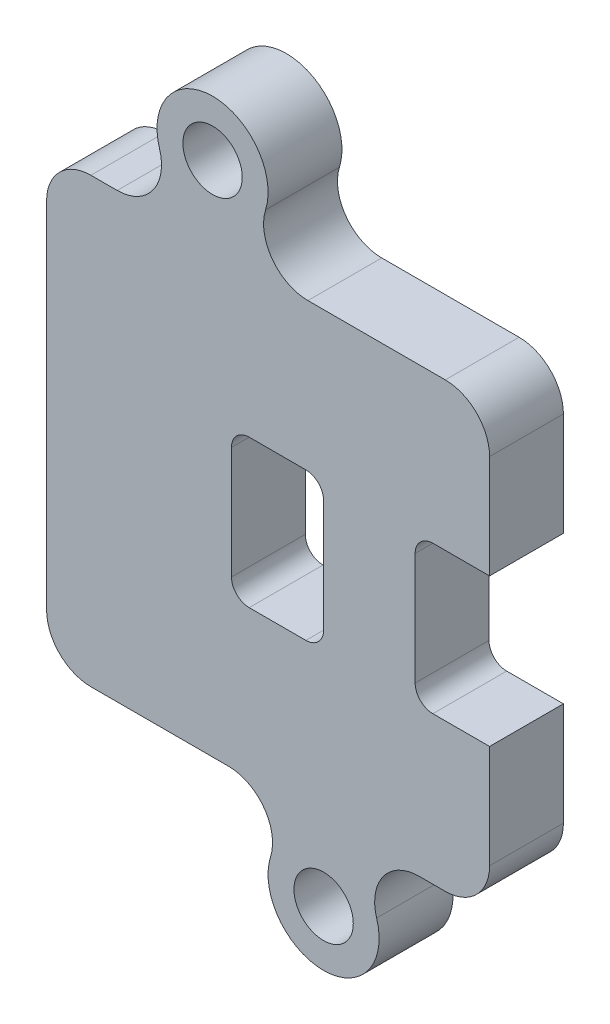
SolidWorks part; units mm, degrees
ref_plane "Front Plane" through (0, 0, 0) normal (0, 0, 1) x (1, 0, 0)
ref_plane "Top Plane" through (0, 0, 0) normal (0, 1, 0) x (1, 0, 0)
ref_plane "Right Plane" through (0, 0, 0) normal (1, 0, 0) x (0, 0, -1)
sketch "Sketch1" plane through (0, 0, 0) normal (0, 0, 1) x (1, 0, 0)
  line L0 (0, 0) -> (38.9585, 0) construction
  line L1 (0, 0) -> (0, -11.6692) construction
  line L2 (0, 0) -> (0, 50.8) construction
  line L3 (-9.5504, 50.8) -> (38.9585, 50.8) construction
  line L4 (-20.0152, 44.45) -> (-17.7513, 44.45)
  line L5 (-23.8252, 40.64) -> (-23.8252, 10.16)
  line L6 (-20.0152, 6.35) -> (-8.2009, 6.35)
  line L7 (14.2748, 40.64) -> (14.2748, 10.16)
  line L8 (-9.5504, 50.8) -> (-9.5504, 15.7719) construction
  line L9 (14.2748, 6.35) -> (14.2748, -14.1884) construction
  line L10 (-7.9248, 31.75) -> (-7.9248, 36.7665) construction
  line L11 (-6.4008, 31.75) -> (-1.524, 31.75)
  line L12 (-7.9248, 30.226) -> (-7.9248, 20.574)
  line L13 (-6.4008, 19.05) -> (-1.524, 19.05)
  line L14 (0, 30.226) -> (0, 20.574)
  line L15 (9.398, 31.75) -> (14.2748, 31.75)
  line L16 (7.874, 30.226) -> (7.874, 20.574)
  line L17 (9.398, 19.05) -> (14.2748, 19.05)
  line L18 (14.2748, 31.75) -> (14.2748, 19.05)
  line L19 (14.2748, 31.75) -> (30.412, 31.75) construction
  line L20 (14.2748, 19.05) -> (25.1773, 19.05) construction
  line L21 (-1.3495, 44.45) -> (10.4648, 44.45)
  line L22 (8.2009, 6.35) -> (10.4648, 6.35)
  circle A0 centre (0, 0) radius 2.5527
  arc A1 (-4.5614, 1.4128) -> (4.5614, 1.4128) centre (0, 0) ccw
  circle A2 centre (-9.5504, 50.8) radius 2.5527
  arc A3 (-4.989, 49.3872) -> (-14.1118, 49.3872) centre (-9.5504, 50.8) ccw
  arc A4 (-1.524, 31.75) -> (0, 30.226) centre (-1.524, 30.226) cw
  arc A5 (-6.4008, 31.75) -> (-7.9248, 30.226) centre (-6.4008, 30.226) ccw
  arc A6 (-7.9248, 20.574) -> (-6.4008, 19.05) centre (-6.4008, 20.574) ccw
  arc A7 (-1.524, 19.05) -> (0, 20.574) centre (-1.524, 20.574) ccw
  arc A8 (7.874, 20.574) -> (9.398, 19.05) centre (9.398, 20.574) ccw
  arc A9 (9.398, 31.75) -> (7.874, 30.226) centre (9.398, 30.226) ccw
  arc A10 (10.4648, 44.45) -> (14.2748, 40.64) centre (10.4648, 40.64) cw
  arc A11 (10.4648, 6.35) -> (14.2748, 10.16) centre (10.4648, 10.16) ccw
  arc A12 (-23.8252, 10.16) -> (-20.0152, 6.35) centre (-20.0152, 10.16) ccw
  arc A13 (-20.0152, 44.45) -> (-23.8252, 40.64) centre (-20.0152, 40.64) ccw
  arc A14 (-1.3495, 44.45) -> (-4.989, 49.3872) centre (-1.3495, 48.26) cw
  arc A15 (-14.1118, 49.3872) -> (-17.7513, 44.45) centre (-17.7513, 48.26) cw
  arc A17 (4.5614, 1.4128) -> (8.2009, 6.35) centre (8.2009, 2.54) cw
  arc A19 (-4.5614, 1.4128) -> (-8.2009, 6.35) centre (-8.2009, 2.54) ccw
  point P3 (38.638, 19.05)
  point P9 (0, -5.8346)
  point P17 (54.9831, 50.8)
  point P31 (0, 31.75)
  point P39 (0, 19.05)
  point P42 (7.874, 19.05)
  point P45 (7.874, 31.75)
  point P53 (-23.8252, 6.35)
  point P68 (27.7412, 19.05)
  point P69 (30.412, 31.75)
  point P70 (25.1773, 19.05)
  point P71 (38.9585, 50.8)
  point P72 (38.9585, 0)
  point P73 (0, -11.6692)
  dimension "D1" = 5.1054
  dimension "D2" = 9.5504
  dimension "D4" = 50.8
  dimension "D9" = 7.9248
  dimension "D12" = 1.524
  dimension "D13" = 3.81
  dimension "D14" = 3.81
  dimension "D3" = 38.1
  dimension "D5" = 6.35
  dimension "D6" = 14.2748
  dimension "D7" = 6.35
  dimension "D8" = 9.5504
  dimension "D10" = 31.75
  dimension "D11" = 19.05
extrude "Boss-Extrude1" add sketch "Sketch1" along normal blind 6.35 contours A19 A1 A17 L22 A11 L7 L17 A8 L16 A9 L15 A10 L21 A14 A3 A15 L4 A13 L5 A12 L6 A7 L13 A6 L12 A5 L11 A4 L14 A2 A0
